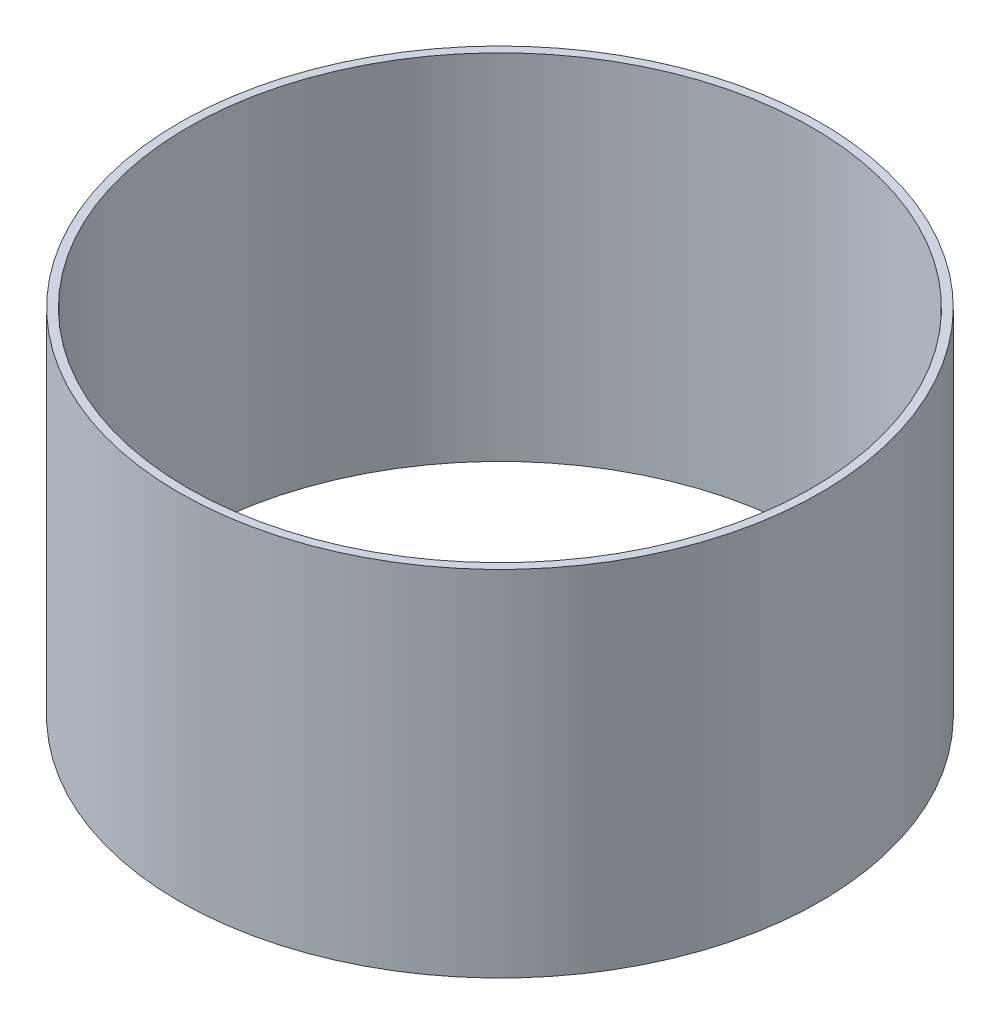
SolidWorks part; units mm, degrees
ref_plane "Front Plane" through (0, 0, 0) normal (0, 0, 1) x (1, 0, 0)
ref_plane "Top Plane" through (0, 0, 0) normal (0, 1, 0) x (1, 0, 0)
ref_plane "Right Plane" through (0, 0, 0) normal (1, 0, 0) x (0, 0, -1)
sketch "Sketch1" plane through (0, 0, 0) normal (0, 1, 0) x (1, 0, 0)
  circle A0 centre (0, 0) radius 38.5
  circle A1 centre (0, 0) radius 37.5
  dimension "D1" = 77
  dimension "D2" = 75
extrude "Boss-Extrude1" add sketch "Sketch1" along normal blind 42.5
